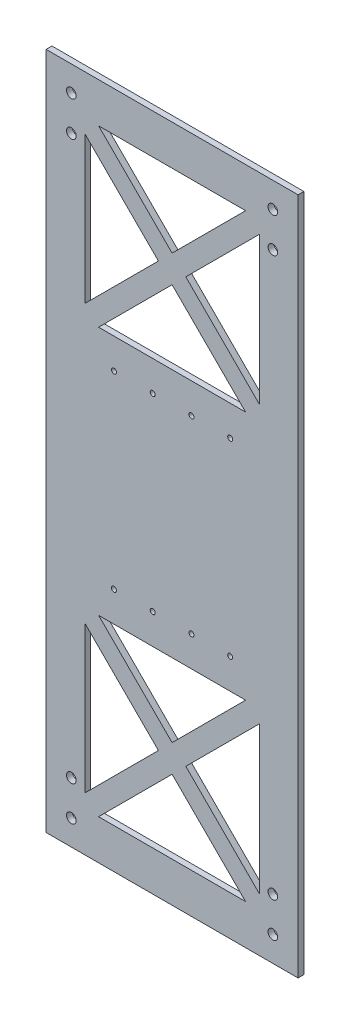
SolidWorks part; units mm, degrees
ref_plane "前基準面" through (0, 0, 0) normal (0, 0, 1) x (1, 0, 0)
ref_plane "上基準面" through (0, 0, 0) normal (0, 1, 0) x (1, 0, 0)
ref_plane "右基準面" through (0, 0, 0) normal (1, 0, 0) x (0, 0, -1)
sketch "草圖1" plane through (0, 0, 0) normal (0, 0, 1) x (1, 0, 0)
  line L0 (0, 175) -> (0, 170) construction
  line L1 (-65, -175) -> (65, -175)
  line L2 (-65, -175) -> (-65, 175)
  line L3 (-65, 175) -> (65, 175)
  line L4 (65, -175) -> (65, 175)
  line L5 (-65, -175) -> (65, 175) construction
  line L6 (-65, 175) -> (65, -175) construction
  line L7 (-30, -48.75) -> (30, -48.75) construction
  line L8 (-30, -48.75) -> (-30, 48.75) construction
  line L9 (-30, 48.75) -> (30, 48.75) construction
  line L10 (30, -48.75) -> (30, 48.75) construction
  line L11 (-30, -48.75) -> (30, 48.75) construction
  line L12 (-30, 48.75) -> (30, -48.75) construction
  line L13 (65, 175) -> (60, 175) construction
  line L14 (60, 175) -> (52, 175) construction
  line L15 (52, 175) -> (52, 162) construction
  line L16 (52, 162) -> (52, 144) construction
  line L17 (0, -175) -> (0, -170) construction
  line L18 (52, -175) -> (52, -162) construction
  line L19 (52, -162) -> (52, -144) construction
  line L22 (0, 170) -> (0, 48.75)
  line L23 (0, -48.75) -> (0, -170) construction
  line L24 (0, -109.375) -> (-50, -59.375) construction
  line L25 (-50, -59.375) -> (50, -59.375) construction
  line L26 (-50, -59.375) -> (-50, -159.375) construction
  line L27 (-50, -159.375) -> (50, -159.375) construction
  line L28 (50, -59.375) -> (50, -159.375) construction
  line L29 (-50, -59.375) -> (50, -159.375) construction
  line L30 (-50, -159.375) -> (50, -59.375) construction
  line L31 (0, -109.375) -> (50, -59.375) construction
  line L32 (0, -109.375) -> (-50, -159.375) construction
  line L33 (0, -109.375) -> (50, -159.375) construction
  line L34 (-37.9289, -64.375) -> (37.9289, -64.375)
  line L35 (0, -102.3039) -> (37.9289, -64.375)
  line L36 (0, -102.3039) -> (-37.9289, -64.375)
  line L37 (-7.0711, -109.375) -> (-45, -71.4461)
  line L38 (-45, -71.4461) -> (-45, -147.3039)
  line L39 (-7.0711, -109.375) -> (-45, -147.3039)
  line L40 (0, -116.4461) -> (37.9289, -154.375)
  line L41 (-37.9289, -154.375) -> (37.9289, -154.375)
  line L42 (0, -116.4461) -> (-37.9289, -154.375)
  line L43 (7.0711, -109.375) -> (45, -71.4461)
  line L44 (45, -71.4461) -> (45, -147.3039)
  line L45 (7.0711, -109.375) -> (45, -147.3039)
  line L46 (-50, 159.375) -> (0, 109.375) construction
  line L47 (-50, 59.375) -> (50, 59.375) construction
  line L48 (-50, 59.375) -> (-50, 159.375) construction
  line L49 (-50, 159.375) -> (50, 159.375) construction
  line L50 (50, 59.375) -> (50, 159.375) construction
  line L51 (-50, 59.375) -> (50, 159.375) construction
  line L52 (-50, 159.375) -> (50, 59.375) construction
  line L53 (-37.9289, 154.375) -> (37.9289, 154.375)
  line L54 (0, 109.375) -> (50, 159.375) construction
  line L55 (0, 109.375) -> (-50, 59.375) construction
  line L56 (0, 109.375) -> (50, 59.375) construction
  line L57 (0, 116.4461) -> (37.9289, 154.375)
  line L58 (-37.9289, 154.375) -> (0, 116.4461)
  line L59 (-45, 147.3039) -> (-7.0711, 109.375)
  line L60 (-7.0711, 109.375) -> (-45, 71.4461)
  line L61 (-45, 71.4461) -> (-45, 147.3039)
  line L62 (0, 102.3039) -> (-37.9289, 64.375)
  line L63 (-37.9289, 64.375) -> (37.9289, 64.375)
  line L64 (0, 102.3039) -> (37.9289, 64.375)
  line L65 (7.0711, 109.375) -> (45, 147.3039)
  line L66 (45, 71.4461) -> (45, 147.3039)
  line L67 (7.0711, 109.375) -> (45, 71.4461)
  line L68 (-65, 175) -> (-60, 175) construction
  line L69 (-60, 175) -> (-52, 175) construction
  line L70 (-52, 175) -> (-52, 162) construction
  line L71 (-52, 162) -> (-52, 144) construction
  line L72 (-65, -175) -> (-60, -175) construction
  line L73 (-60, -175) -> (-52, -175) construction
  line L74 (-52, -175) -> (-52, -162) construction
  line L75 (-52, -162) -> (-52, -144) construction
  line L76 (65, -175) -> (60, -175) construction
  line L77 (60, -175) -> (52, -175) construction
  circle A0 centre (-30, 48.75) radius 1.3
  circle A1 centre (-10, 48.75) radius 1.3
  circle A2 centre (10, 48.75) radius 1.3
  circle A3 centre (30, 48.75) radius 1.3
  circle A4 centre (-30, -48.75) radius 1.3
  circle A5 centre (-10, -48.75) radius 1.3
  circle A6 centre (10, -48.75) radius 1.3
  circle A7 centre (30, -48.75) radius 1.3
  circle A8 centre (-52, -162) radius 2.5
  circle A9 centre (-52, -144) radius 2.5
  circle A10 centre (52, -144) radius 2.5
  circle A11 centre (52, -162) radius 2.5
  circle A12 centre (52, 162) radius 2.5
  circle A13 centre (52, 144) radius 2.5
  circle A14 centre (-52, 162) radius 2.5
  circle A15 centre (-52, 144) radius 2.5
  point P0 (0, 0)
  point P6 (0, 0)
  point P11 (-10, 48.75)
  point P12 (10, 48.75)
  point P13 (-10, -48.75)
  point P14 (10, -48.75)
  point P49 (0, -109.375)
  point P67 (0, 109.375)
  dimension "D5" = 2.6
  dimension "D9" = 13
  dimension "D23" = 5
  dimension "D1" = 130
  dimension "D2" = 350
  dimension "D3" = 60
  dimension "D4" = 97.5
  dimension "D6" = 5
  dimension "D7" = 5
  dimension "D8" = 8
  dimension "D12" = 100
  dimension "D13" = 100
  dimension "D16" = 100
  dimension "D17" = 100
  dimension "D22" = 18
  dimension "D10" = 5
  dimension "D11" = 5
  dimension "D14" = 5
  dimension "D15" = 5
  dimension "D18" = 5
  dimension "D19" = 5
  dimension "D20" = 5
  dimension "D21" = 5
extrude "填料-伸長1" add sketch "草圖1" along normal blind 3
